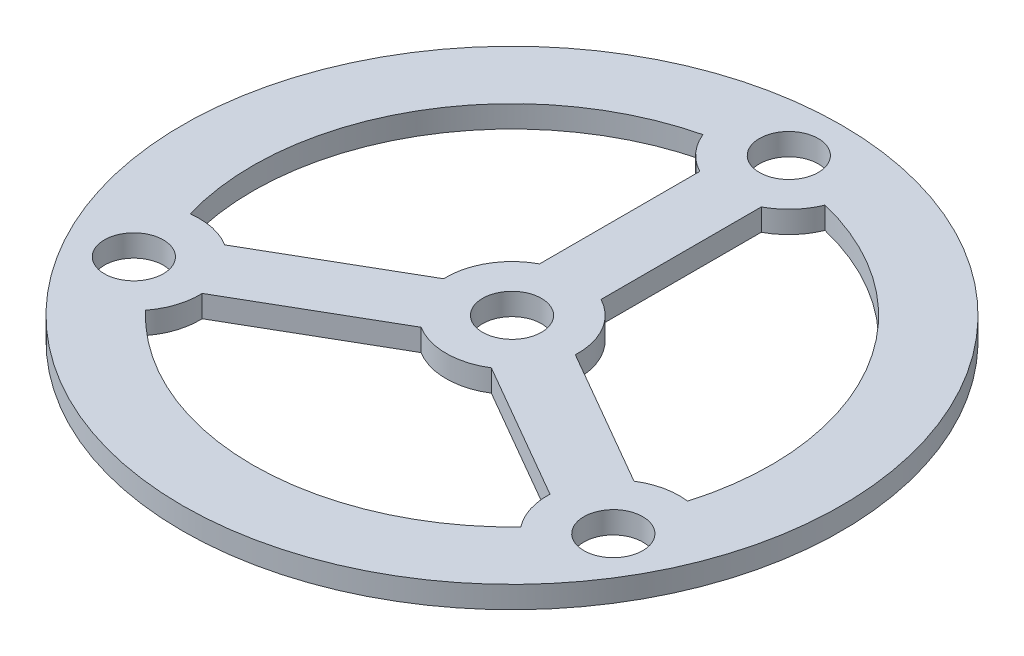
SolidWorks part; units mm, degrees
material "ABS PC"
ref_plane "Front Plane" through (0, 0, 0) normal (0, 0, 1) x (1, 0, 0)
ref_plane "Top Plane" through (0, 0, 0) normal (0, 1, 0) x (1, 0, 0)
ref_plane "Right Plane" through (0, 0, 0) normal (1, 0, 0) x (0, 0, -1)
sketch "Sketch1" plane through (0, 0, 0) normal (0, 1, 0) x (1, 0, 0)
  circle A0 centre (0, 0) radius 37.5
  arc A1 (-6.9458, 28.6706) -> (-28.3024, -8.32) centre (0, 0) ccw
  arc A2 (-6.9458, 28.6706) -> (6.9458, 28.6706) centre (0, 31.5) ccw
  circle A3 centre (0, 31.5) radius 3.35
  arc A4 (28.3024, -8.32) -> (21.3566, -20.3506) centre (27.2798, -15.75) ccw
  circle A5 centre (27.2798, -15.75) radius 3.35
  arc A6 (-21.3566, -20.3506) -> (-28.3024, -8.32) centre (-27.2798, -15.75) ccw
  circle A7 centre (-27.2798, -15.75) radius 3.35
  arc A8 (28.3024, -8.32) -> (6.9458, 28.6706) centre (0, 0) ccw
  arc A9 (-21.3566, -20.3506) -> (21.3566, -20.3506) centre (0, 0) ccw
  point P18 (0, 0)
  dimension "D1" = 75
  dimension "D2" = 8
  dimension "D3" = 6.7
  dimension "D4" = 15
  dimension "D5" = 31.5
  dimension "D6" = 3
extrude "Boss-Extrude1" add sketch "Sketch1" along normal blind 2.5
sketch "Sketch2" plane through (0, 0, 0) normal (0, 1, 0) x (1, 0, 0)
  line L0 (3.5, 6.6332) -> (3.5, 31.5)
  line L1 (-7.4946, -0.2855) -> (-29.0298, -12.7189)
  line L2 (-3.9946, -6.3477) -> (-25.5298, -18.7811)
  line L3 (-1.75, 3.0311) -> (-1.675, 2.9012)
  line L4 (-29.0298, -12.7189) -> (-28.9548, -12.8488)
  line L5 (-25.6048, -18.6512) -> (-25.5298, -18.7811)
  line L6 (1.675, -2.9012) -> (1.75, -3.0311)
  line L7 (-3.5, 6.6332) -> (-3.5, 31.5)
  line L8 (3.5, 31.5) -> (3.35, 31.5)
  line L9 (-3.35, 31.5) -> (-3.5, 31.5)
  line L10 (3.9946, -6.3477) -> (25.5298, -18.7811)
  line L11 (7.4946, -0.2855) -> (29.0298, -12.7189)
  line L12 (25.5298, -18.7811) -> (25.6048, -18.6512)
  line L13 (28.9548, -12.8488) -> (29.0298, -12.7189)
  circle A0 centre (0, 0) radius 7.5
  circle A1 centre (0, 0) radius 3.35
  arc A2 (-3.35, 31.5) -> (3.35, 31.5) centre (0, 31.5) ccw
  arc A3 (-25.6048, -18.6512) -> (-28.9548, -12.8488) centre (-27.2798, -15.75) ccw
  arc A4 (28.9548, -12.8488) -> (25.6048, -18.6512) centre (27.2798, -15.75) ccw
  point P32 (0, 0)
  point P34 (0, 0)
  dimension "D1" = 6.7
  dimension "D2" = 15
  dimension "D3" = 0.1299
  dimension "D4" = 3
extrude "Boss-Extrude2" add sketch "Sketch2" along normal blind 2.5
